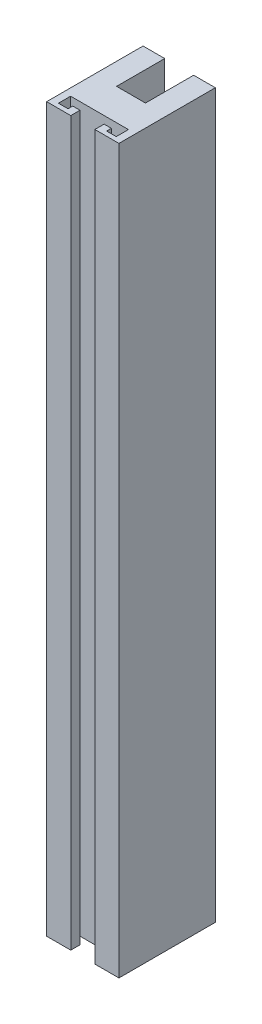
SolidWorks part; units mm, degrees
material "Aço inoxidável forjado"
ref_plane "Plano frontal" through (0, 0, 0) normal (0, 0, 1) x (1, 0, 0)
ref_plane "Plano superior" through (0, 0, 0) normal (0, 1, 0) x (1, 0, 0)
ref_plane "Plano direito" through (0, 0, 0) normal (1, 0, 0) x (0, 0, -1)
sketch "Esboço1" plane through (0, 0, 0) normal (0, 1, 0) x (1, 0, 0)
  line L5 (3, 7.5) -> (7.5, 7.5)
  line L11 (-7.5, -7.5) -> (-7.5, 7.5)
  line L12 (-7.5, 7.5) -> (-3, 7.5)
  line L13 (7.5, -7.5) -> (7.5, 7.5)
  line L14 (-2.5, -12.5047) -> (-2.5, -10.5851)
  line L15 (-7.5, 7.5) -> (7.5, -7.5) construction
  line L16 (-3, -2.5) -> (3, -2.5)
  line L17 (-3, -2.5) -> (-3, 7.5)
  line L19 (3, -2.5) -> (3, 7.5)
  line L43 (-7.5, -7.5) -> (-7.5, -12.5047)
  line L44 (-7.5, -12.5047) -> (-2.5, -12.5047)
  line L45 (-2.5, -10.5851) -> (-4, -10.5851)
  line L46 (7.5, -7.5) -> (7.5, -12.5047)
  line L47 (7.5, -12.5047) -> (2.5, -12.5047)
  line L48 (-4, -10.5851) -> (-4, -11.5647)
  line L49 (-4, -11.5647) -> (-6, -11.5647)
  line L50 (-6, -11.5647) -> (-6, -9.0361)
  line L51 (2.5, -12.5047) -> (2.5, -10.5847)
  line L52 (2.5, -10.5847) -> (4, -10.5847)
  line L53 (4, -10.5847) -> (4, -11.5667)
  line L54 (4, -11.5667) -> (6, -11.5667)
  line L55 (6, -11.5667) -> (6, -9.0361)
  line L56 (6, -9.0361) -> (-6, -9.0361)
  point P0 (0, 0)
  point P6 (0, 7.5)
  dimension "D3" = 10
  dimension "D1" = 20.0047
  dimension "D2" = 1.5
  dimension "D4" = 1.5
  dimension "D5" = 2
  dimension "D6" = 20.0047
  dimension "D7" = 1.5
  dimension "D8" = 0.938
  dimension "D9" = 0.94
  dimension "D10" = 1.92
extrude "Ressalto-extrusão1" add sketch "Esboço1" along normal blind 150
